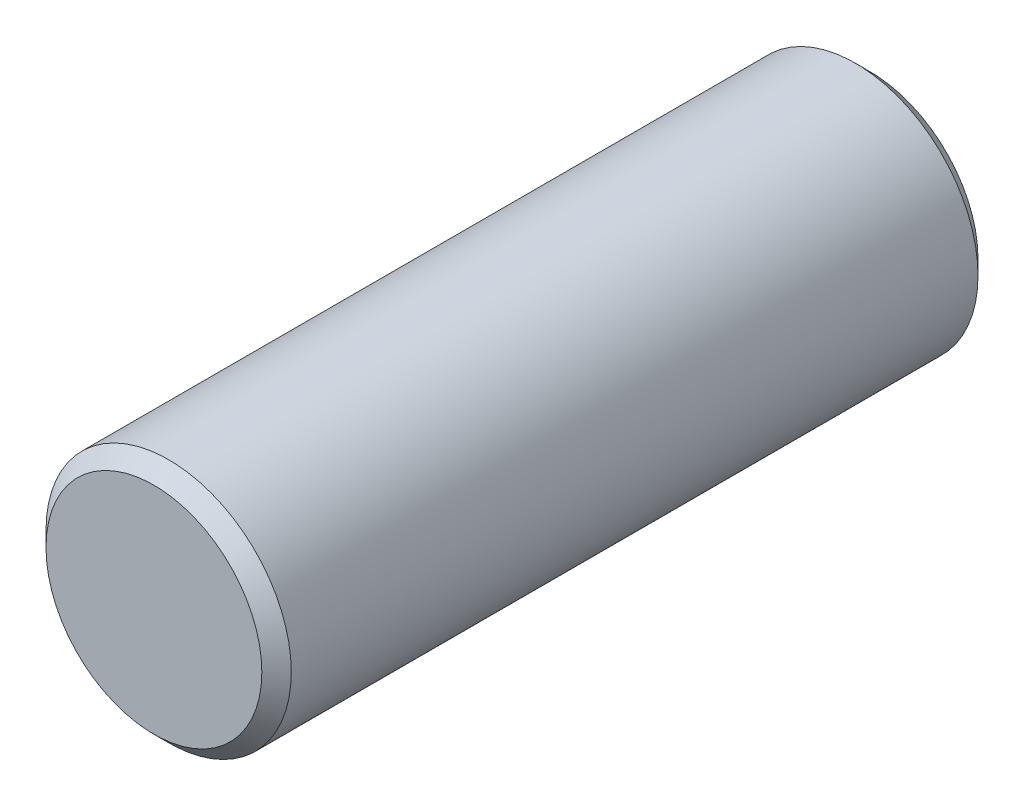
SolidWorks part; units mm, degrees
material "1.4305 (X8CrNiS18-9)"
ref_plane "Ebene1" through (0, 0, 0) normal (0, 0, 1) x (1, 0, 0)
ref_plane "Ebene2" through (0, 0, 0) normal (0, 1, 0) x (1, 0, 0)
ref_plane "Ebene3" through (0, 0, 0) normal (1, 0, 0) x (0, 0, -1)
sketch "Skizze1" plane through (0, 0, 0) normal (0, 0, 1) x (1, 0, 0)
  circle A0 centre (0, 0) radius 12.5
  dimension "D1" = 25
extrude "Basis-Linear austragen" add sketch "Skizze1" along normal mid plane 73
chamfer "Fase1" distance 1.5 angle 45 2 edges at (12.5, 0, -36.5) (12.5, 0, 36.5)
